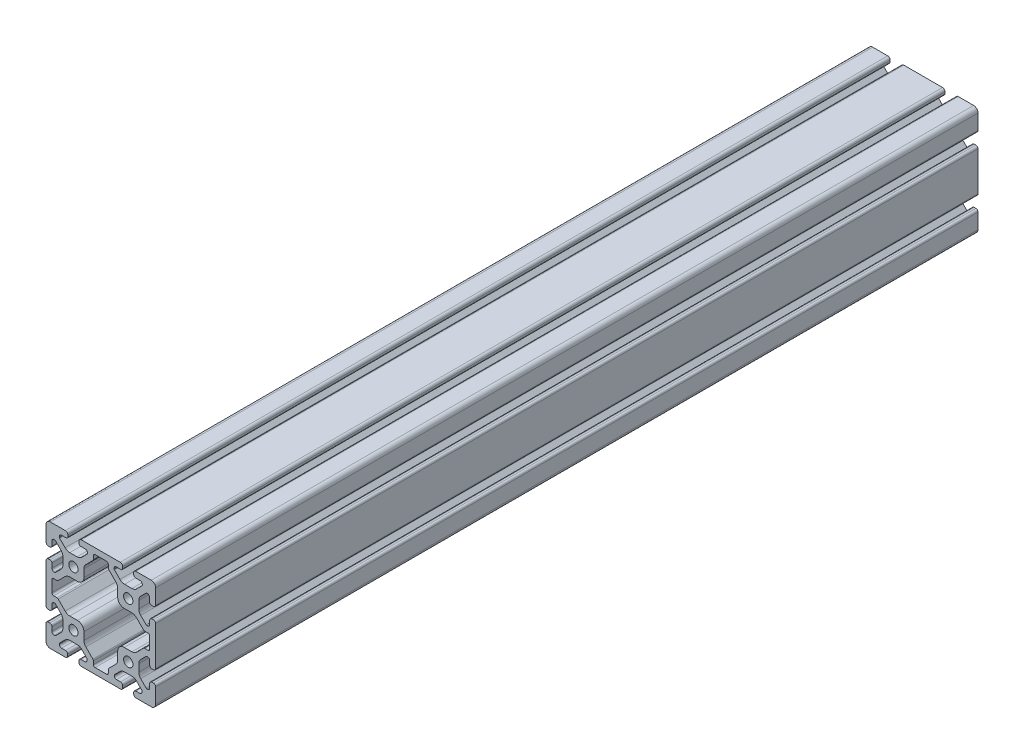
SolidWorks part; units mm, degrees
material "6061 Alloy"
ref_plane "Front Plane" through (0, 0, 0) normal (0, 0, 1) x (1, 0, 0)
ref_plane "Top Plane" through (0, 0, 0) normal (0, 1, 0) x (1, 0, 0)
ref_plane "Right Plane" through (0, 0, 0) normal (1, 0, 0) x (0, 0, -1)
sketch "Sketch1" plane through (0, 0, 0) normal (0, 0, 1) x (1, 0, 0)
  line L0 (0, -40) -> (0, 40) construction
  line L1 (0, 0) -> (-43.5804, 43.5804) construction
  line L2 (-20, 20) -> (-47.7323, 20) construction
  line L3 (-20, 20) -> (3.796, 43.796) construction
  line L4 (-20, 20) -> (-20, 43.5758) construction
  line L5 (-20, -27.7) -> (-20, -47.5576) construction
  line L131 (29.0912, 26.0365) -> (33.0827, 30.028)
  line L132 (27.7, 17.3222) -> (27.7, 22.6778)
  line L133 (29.0912, 13.9635) -> (33.0827, 9.972)
  line L134 (33.6201, 9.7494) -> (34.11, 9.7494)
  line L135 (35.68, 11.3194) -> (35.68, 14.2221)
  line L136 (37.25, 15.7921) -> (38.43, 15.7921)
  line L137 (40, 14.2221) -> (40, 7.0214)
  line L138 (40, 7.0214) -> (40, -7.0214)
  line L139 (40, -7.0214) -> (40, -14.2221)
  line L140 (38.43, -15.7921) -> (37.25, -15.7921)
  line L141 (35.68, -14.2221) -> (35.68, -11.3194)
  line L142 (33.6201, -9.7494) -> (34.11, -9.7494)
  line L143 (29.0912, -13.9635) -> (33.0827, -9.972)
  line L144 (27.7, -22.6778) -> (27.7, -17.3222)
  line L145 (29.0912, -26.0365) -> (33.0827, -30.028)
  line L146 (33.6201, -30.2506) -> (34.11, -30.2506)
  line L147 (35.68, -28.6806) -> (35.68, -25.7779)
  line L148 (37.25, -24.2079) -> (38.43, -24.2079)
  line L149 (40, -25.7779) -> (40, -33.0259)
  line L150 (40, -33.0259) -> (40, -36.83)
  line L151 (36.83, -40) -> (32.9998, -40)
  line L152 (32.9998, -40) -> (25.5696, -40)
  line L153 (23.9996, -38.43) -> (23.9996, -37.25)
  line L154 (25.5696, -35.68) -> (28.4723, -35.68)
  line L155 (30.0413, -34.0552) -> (30.0171, -33.3605)
  line L156 (29.7949, -32.8496) -> (26.0365, -29.0912)
  line L157 (17.3222, -27.7) -> (22.6778, -27.7)
  line L158 (10.035, -33.0197) -> (13.9635, -29.0912)
  line L159 (9.8124, -33.8926) -> (9.8124, -33.5571)
  line L160 (11.3824, -35.4626) -> (14.4246, -35.4626)
  line L161 (15.9946, -37.0326) -> (15.9946, -38.43)
  line L162 (14.4246, -40) -> (6.9987, -40)
  line L163 (6.9987, -40) -> (-6.9987, -40)
  line L164 (-6.9987, -40) -> (-14.4292, -40)
  line L165 (-15.9992, -38.43) -> (-15.9992, -37.25)
  line L166 (-14.4292, -35.68) -> (-11.5265, -35.68)
  line L167 (-9.9574, -34.0552) -> (-9.9816, -33.3618)
  line L168 (-10.2038, -32.8509) -> (-13.9635, -29.0912)
  line L169 (-22.6778, -27.7) -> (-17.3222, -27.7)
  line L170 (-30.028, -33.0827) -> (-26.0365, -29.0912)
  line L171 (-30.2506, -34.11) -> (-30.2506, -33.6201)
  line L172 (-28.6806, -35.68) -> (-25.7231, -35.68)
  line L173 (-24.1531, -37.25) -> (-24.1531, -38.43)
  line L174 (-25.7231, -40) -> (-33, -40)
  line L175 (-33, -40) -> (-36.83, -40)
  line L176 (-40, -36.83) -> (-40, -33.0191)
  line L177 (-40, -33.0191) -> (-40, -25.591)
  line L178 (-38.43, -24.021) -> (-37.25, -24.021)
  line L179 (-35.68, -28.4937) -> (-35.68, -25.591)
  line L180 (-34.0552, -30.0627) -> (-33.3827, -30.0392)
  line L181 (-32.8718, -29.8171) -> (-29.0912, -26.0365)
  line L182 (-27.7, -22.6778) -> (-27.7, -17.3222)
  line L183 (-29.0912, -13.9635) -> (-33.0827, -9.972)
  line L184 (-34.11, -9.7494) -> (-33.6201, -9.7494)
  line L185 (-35.68, -11.3194) -> (-35.68, -14.4473)
  line L186 (-38.43, -16.0173) -> (-37.25, -16.0173)
  line L187 (-40, -14.4473) -> (-40, -7.0169)
  line L188 (-40, -7.0169) -> (-40, 7.0169)
  line L189 (-40, 7.0169) -> (-40, 14.1348)
  line L190 (-38.1948, 15.94) -> (-36.9772, 15.94)
  line L191 (-35.68, 11.3194) -> (-35.68, 14.6428)
  line L192 (-34.11, 9.7494) -> (-33.6201, 9.7494)
  line L193 (-33.0827, 9.972) -> (-29.0912, 13.9635)
  line L194 (-27.7, 17.3222) -> (-27.7, 22.6778)
  line L195 (-29.0912, 26.0365) -> (-33.0827, 30.028)
  line L196 (-34.11, 30.2506) -> (-33.6201, 30.2506)
  line L197 (-35.68, 28.6806) -> (-35.68, 25.3572)
  line L198 (-38.1948, 24.06) -> (-36.9772, 24.06)
  line L199 (-40, 25.8652) -> (-40, 33.3181)
  line L200 (-40, 33.3181) -> (-40, 36.83)
  line L201 (-36.83, 40) -> (-33.0314, 40)
  line L202 (-33.0314, 40) -> (-25.8652, 40)
  line L203 (-24.06, 36.9772) -> (-24.06, 38.1948)
  line L204 (-25.3572, 35.68) -> (-28.7018, 35.68)
  line L205 (-30.285, 33.6069) -> (-30.285, 34.0968)
  line L206 (-30.0961, 33.1508) -> (-26.0365, 29.0912)
  line L207 (-22.6778, 27.7) -> (-17.3222, 27.7)
  line L208 (-13.9635, 29.0912) -> (-9.9039, 33.1508)
  line L209 (-9.715, 33.6069) -> (-9.715, 34.0968)
  line L210 (-14.6428, 35.68) -> (-11.2982, 35.68)
  line L211 (-15.94, 36.9772) -> (-15.94, 38.1948)
  line L212 (-14.1348, 40) -> (-6.9844, 40)
  line L213 (-6.9844, 40) -> (6.9844, 40)
  line L214 (6.9844, 40) -> (14.1348, 40)
  line L215 (15.94, 36.9772) -> (15.94, 38.1948)
  line L216 (14.6428, 35.68) -> (11.2982, 35.68)
  line L217 (9.715, 33.6069) -> (9.715, 34.0968)
  line L218 (9.9039, 33.1508) -> (13.9635, 29.0912)
  line L219 (17.3222, 27.7) -> (22.6778, 27.7)
  line L220 (26.0365, 29.0912) -> (30.028, 33.0827)
  line L221 (30.2506, 33.6201) -> (30.2506, 34.11)
  line L222 (25.5409, 35.679) -> (28.6258, 35.679)
  line L223 (23.9709, 37.249) -> (23.9709, 38.43)
  line L224 (25.5409, 40) -> (36.83, 40)
  line L226 (40, 36.83) -> (40, 32.9339)
  line L227 (40, 32.9339) -> (40, 25.7779)
  line L228 (38.43, 24.2079) -> (37.0956, 24.2079)
  line L229 (35.5256, 25.7779) -> (35.5256, 28.6806)
  line L230 (33.6201, 30.2506) -> (33.9556, 30.2506)
  line L231 (17.07, 12.32) -> (22.6578, 12.32)
  line L232 (26.0165, 10.9288) -> (31.1439, 5.8014)
  line L233 (32.0419, 5.4294) -> (34.41, 5.4294)
  line L234 (35.68, -4.1594) -> (35.68, 4.1594)
  line L235 (32.0419, -5.4294) -> (34.41, -5.4294)
  line L236 (26.0165, -10.9288) -> (31.1439, -5.8014)
  line L237 (17.07, -12.32) -> (22.6578, -12.32)
  line L238 (12.32, -22.6578) -> (12.32, -17.07)
  line L239 (5.8014, -31.1439) -> (10.9288, -26.0165)
  line L240 (5.4294, -34.41) -> (5.4294, -32.0419)
  line L241 (-4.1594, -35.68) -> (4.1594, -35.68)
  line L242 (-5.4294, -34.41) -> (-5.4294, -32.0419)
  line L243 (-5.8014, -31.1439) -> (-10.9288, -26.0165)
  line L244 (-12.32, -22.6578) -> (-12.32, -17.07)
  line L245 (-22.6578, -12.32) -> (-17.07, -12.32)
  line L246 (-26.0165, -10.9288) -> (-31.1439, -5.8014)
  line L247 (-34.41, -5.4294) -> (-32.0419, -5.4294)
  line L248 (-35.68, -4.1594) -> (-35.68, 4.1594)
  line L249 (-34.41, 5.4294) -> (-32.0419, 5.4294)
  line L250 (-31.1439, 5.8014) -> (-26.0165, 10.9288)
  line L251 (-22.6578, 12.32) -> (-17.07, 12.32)
  line L252 (-12.32, 17.07) -> (-12.32, 22.6578)
  line L253 (-10.9288, 26.0165) -> (-5.8014, 31.1439)
  line L254 (-5.4294, 32.0419) -> (-5.4294, 34.41)
  line L255 (-4.1594, 35.68) -> (4.1594, 35.68)
  line L256 (5.4294, 32.0419) -> (5.4294, 34.41)
  line L257 (5.8014, 31.1439) -> (10.9288, 26.0165)
  line L258 (12.32, 17.07) -> (12.32, 22.6578)
  line L260 (-40, 0) -> (40, 0) construction
  circle A116 centre (-20, 20) radius 3.4
  circle A117 centre (20, 20) radius 3.4
  circle A118 centre (20, -20) radius 3.4
  circle A119 centre (-20, -20) radius 3.4
  arc A120 (29.0912, 26.0365) -> (27.7, 22.6778) centre (32.45, 22.6778) ccw
  arc A121 (27.7, 17.3222) -> (29.0912, 13.9635) centre (32.45, 17.3222) ccw
  arc A122 (33.0827, 9.972) -> (33.6201, 9.7494) centre (33.6201, 10.5094) ccw
  arc A123 (34.11, 9.7494) -> (35.68, 11.3194) centre (34.11, 11.3194) ccw
  arc A124 (37.25, 15.7921) -> (35.68, 14.2221) centre (37.25, 14.2221) ccw
  arc A125 (40, 14.2221) -> (38.43, 15.7921) centre (38.43, 14.2221) ccw
  arc A126 (38.43, -15.7921) -> (40, -14.2221) centre (38.43, -14.2221) ccw
  arc A127 (35.68, -14.2221) -> (37.25, -15.7921) centre (37.25, -14.2221) ccw
  arc A128 (35.68, -11.3194) -> (34.11, -9.7494) centre (34.11, -11.3194) ccw
  arc A129 (33.6201, -9.7494) -> (33.0827, -9.972) centre (33.6201, -10.5094) ccw
  arc A130 (29.0912, -13.9635) -> (27.7, -17.3222) centre (32.45, -17.3222) ccw
  arc A131 (27.7, -22.6778) -> (29.0912, -26.0365) centre (32.45, -22.6778) ccw
  arc A132 (33.0827, -30.028) -> (33.6201, -30.2506) centre (33.6201, -29.4906) ccw
  arc A133 (34.11, -30.2506) -> (35.68, -28.6806) centre (34.11, -28.6806) ccw
  arc A134 (37.25, -24.2079) -> (35.68, -25.7779) centre (37.25, -25.7779) ccw
  arc A135 (40, -25.7779) -> (38.43, -24.2079) centre (38.43, -25.7779) ccw
  arc A136 (36.83, -40) -> (40, -36.83) centre (36.83, -36.83) ccw
  arc A137 (23.9996, -38.43) -> (25.5696, -40) centre (25.5696, -38.43) ccw
  arc A138 (25.5696, -35.68) -> (23.9996, -37.25) centre (25.5696, -37.25) ccw
  arc A139 (28.4723, -35.68) -> (30.0413, -34.0552) centre (28.4723, -34.11) ccw
  arc A140 (30.0171, -33.3605) -> (29.7949, -32.8496) centre (29.2575, -33.387) ccw
  arc A141 (26.0365, -29.0912) -> (22.6778, -27.7) centre (22.6778, -32.45) ccw
  arc A142 (17.3222, -27.7) -> (13.9635, -29.0912) centre (17.3222, -32.45) ccw
  arc A143 (10.035, -33.0197) -> (9.8124, -33.5571) centre (10.5724, -33.5571) ccw
  arc A144 (9.8124, -33.8926) -> (11.3824, -35.4626) centre (11.3824, -33.8926) ccw
  arc A145 (15.9946, -37.0326) -> (14.4246, -35.4626) centre (14.4246, -37.0326) ccw
  arc A146 (14.4246, -40) -> (15.9946, -38.43) centre (14.4246, -38.43) ccw
  arc A147 (-15.9992, -38.43) -> (-14.4292, -40) centre (-14.4292, -38.43) ccw
  arc A148 (-14.4292, -35.68) -> (-15.9992, -37.25) centre (-14.4292, -37.25) ccw
  arc A149 (-11.5265, -35.68) -> (-9.9574, -34.0552) centre (-11.5265, -34.11) ccw
  arc A150 (-9.9816, -33.3618) -> (-10.2038, -32.8509) centre (-10.7412, -33.3883) ccw
  arc A151 (-13.9635, -29.0912) -> (-17.3222, -27.7) centre (-17.3222, -32.45) ccw
  arc A152 (-22.6778, -27.7) -> (-26.0365, -29.0912) centre (-22.6778, -32.45) ccw
  arc A153 (-30.028, -33.0827) -> (-30.2506, -33.6201) centre (-29.4906, -33.6201) ccw
  arc A154 (-30.2506, -34.11) -> (-28.6806, -35.68) centre (-28.6806, -34.11) ccw
  arc A155 (-24.1531, -37.25) -> (-25.7231, -35.68) centre (-25.7231, -37.25) ccw
  arc A156 (-25.7231, -40) -> (-24.1531, -38.43) centre (-25.7231, -38.43) ccw
  arc A157 (-40, -36.83) -> (-36.83, -40) centre (-36.83, -36.83) ccw
  arc A158 (-38.43, -24.021) -> (-40, -25.591) centre (-38.43, -25.591) ccw
  arc A159 (-35.68, -25.591) -> (-37.25, -24.021) centre (-37.25, -25.591) ccw
  arc A160 (-35.68, -28.4937) -> (-34.0552, -30.0627) centre (-34.11, -28.4937) ccw
  arc A161 (-33.3827, -30.0392) -> (-32.8718, -29.8171) centre (-33.4092, -29.2797) ccw
  arc A162 (-29.0912, -26.0365) -> (-27.7, -22.6778) centre (-32.45, -22.6778) ccw
  arc A163 (-27.7, -17.3222) -> (-29.0912, -13.9635) centre (-32.45, -17.3222) ccw
  arc A164 (-33.0827, -9.972) -> (-33.6201, -9.7494) centre (-33.6201, -10.5094) ccw
  arc A165 (-34.11, -9.7494) -> (-35.68, -11.3194) centre (-34.11, -11.3194) ccw
  arc A166 (-37.25, -16.0173) -> (-35.68, -14.4473) centre (-37.25, -14.4473) ccw
  arc A167 (-40, -14.4473) -> (-38.43, -16.0173) centre (-38.43, -14.4473) ccw
  arc A168 (-38.1948, 15.94) -> (-40, 14.1348) centre (-38.1948, 14.1348) ccw
  arc A169 (-35.68, 14.6428) -> (-36.9772, 15.94) centre (-36.9772, 14.6428) ccw
  arc A170 (-35.68, 11.3194) -> (-34.11, 9.7494) centre (-34.11, 11.3194) ccw
  arc A171 (-33.6201, 9.7494) -> (-33.0827, 9.972) centre (-33.6201, 10.5094) ccw
  arc A172 (-29.0912, 13.9635) -> (-27.7, 17.3222) centre (-32.45, 17.3222) ccw
  arc A173 (-27.7, 22.6778) -> (-29.0912, 26.0365) centre (-32.45, 22.6778) ccw
  arc A174 (-33.0827, 30.028) -> (-33.6201, 30.2506) centre (-33.6201, 29.4906) ccw
  arc A175 (-34.11, 30.2506) -> (-35.68, 28.6806) centre (-34.11, 28.6806) ccw
  arc A176 (-36.9772, 24.06) -> (-35.68, 25.3572) centre (-36.9772, 25.3572) ccw
  arc A177 (-40, 25.8652) -> (-38.1948, 24.06) centre (-38.1948, 25.8652) ccw
  arc A178 (-36.83, 40) -> (-40, 36.83) centre (-36.83, 36.83) ccw
  arc A179 (-24.06, 38.1948) -> (-25.8652, 40) centre (-25.8652, 38.1948) ccw
  arc A180 (-25.3572, 35.68) -> (-24.06, 36.9772) centre (-25.3572, 36.9772) ccw
  arc A181 (-28.7018, 35.68) -> (-30.285, 34.0968) centre (-28.7018, 34.0968) ccw
  arc A182 (-30.285, 33.6069) -> (-30.0961, 33.1508) centre (-29.6399, 33.6069) ccw
  arc A183 (-26.0365, 29.0912) -> (-22.6778, 27.7) centre (-22.6778, 32.45) ccw
  arc A184 (-17.3222, 27.7) -> (-13.9635, 29.0912) centre (-17.3222, 32.45) ccw
  arc A185 (-9.9039, 33.1508) -> (-9.715, 33.6069) centre (-10.3601, 33.6069) ccw
  arc A186 (-9.715, 34.0968) -> (-11.2982, 35.68) centre (-11.2982, 34.0968) ccw
  arc A187 (-15.94, 36.9772) -> (-14.6428, 35.68) centre (-14.6428, 36.9772) ccw
  arc A188 (-14.1348, 40) -> (-15.94, 38.1948) centre (-14.1348, 38.1948) ccw
  arc A189 (15.94, 38.1948) -> (14.1348, 40) centre (14.1348, 38.1948) ccw
  arc A190 (14.6428, 35.68) -> (15.94, 36.9772) centre (14.6428, 36.9772) ccw
  arc A191 (11.2982, 35.68) -> (9.715, 34.0968) centre (11.2982, 34.0968) ccw
  arc A192 (9.715, 33.6069) -> (9.9039, 33.1508) centre (10.3601, 33.6069) ccw
  arc A193 (13.9635, 29.0912) -> (17.3222, 27.7) centre (17.3222, 32.45) ccw
  arc A194 (22.6778, 27.7) -> (26.0365, 29.0912) centre (22.6778, 32.45) ccw
  arc A195 (30.028, 33.0827) -> (30.2506, 33.6201) centre (29.4906, 33.6201) ccw
  arc A196 (30.2506, 34.11) -> (28.6258, 35.679) centre (28.6806, 34.11) ccw
  arc A197 (23.9709, 37.249) -> (25.5409, 35.679) centre (25.5409, 37.249) ccw
  arc A198 (25.5409, 40) -> (23.9709, 38.43) centre (25.5409, 38.43) ccw
  arc A199 (40, 36.83) -> (36.83, 40) centre (36.83, 36.83) ccw
  arc A200 (38.43, 24.2079) -> (40, 25.7779) centre (38.43, 25.7779) ccw
  arc A201 (35.5256, 25.7779) -> (37.0956, 24.2079) centre (37.0956, 25.7779) ccw
  arc A202 (35.5256, 28.6806) -> (33.9556, 30.2506) centre (33.9556, 28.6806) ccw
  arc A203 (33.6201, 30.2506) -> (33.0827, 30.028) centre (33.6201, 29.4906) ccw
  arc A204 (26.0165, 10.9288) -> (22.6578, 12.32) centre (22.6578, 7.57) ccw
  arc A205 (31.1439, 5.8014) -> (32.0419, 5.4294) centre (32.0419, 6.6994) ccw
  arc A206 (35.68, 4.1594) -> (34.41, 5.4294) centre (34.41, 4.1594) ccw
  arc A207 (34.41, -5.4294) -> (35.68, -4.1594) centre (34.41, -4.1594) ccw
  arc A208 (32.0419, -5.4294) -> (31.1439, -5.8014) centre (32.0419, -6.6994) ccw
  arc A209 (22.6578, -12.32) -> (26.0165, -10.9288) centre (22.6578, -7.57) ccw
  arc A210 (17.07, -12.32) -> (12.32, -17.07) centre (17.07, -17.07) ccw
  arc A211 (10.9288, -26.0165) -> (12.32, -22.6578) centre (7.57, -22.6578) ccw
  arc A212 (5.8014, -31.1439) -> (5.4294, -32.0419) centre (6.6994, -32.0419) ccw
  arc A213 (4.1594, -35.68) -> (5.4294, -34.41) centre (4.1594, -34.41) ccw
  arc A214 (-5.4294, -34.41) -> (-4.1594, -35.68) centre (-4.1594, -34.41) ccw
  arc A215 (-5.4294, -32.0419) -> (-5.8014, -31.1439) centre (-6.6994, -32.0419) ccw
  arc A216 (-12.32, -22.6578) -> (-10.9288, -26.0165) centre (-7.57, -22.6578) ccw
  arc A217 (-12.32, -17.07) -> (-17.07, -12.32) centre (-17.07, -17.07) ccw
  arc A218 (-26.0165, -10.9288) -> (-22.6578, -12.32) centre (-22.6578, -7.57) ccw
  arc A219 (-31.1439, -5.8014) -> (-32.0419, -5.4294) centre (-32.0419, -6.6994) ccw
  arc A220 (-35.68, -4.1594) -> (-34.41, -5.4294) centre (-34.41, -4.1594) ccw
  arc A221 (-34.41, 5.4294) -> (-35.68, 4.1594) centre (-34.41, 4.1594) ccw
  arc A222 (-32.0419, 5.4294) -> (-31.1439, 5.8014) centre (-32.0419, 6.6994) ccw
  arc A223 (-22.6578, 12.32) -> (-26.0165, 10.9288) centre (-22.6578, 7.57) ccw
  arc A224 (-17.07, 12.32) -> (-12.32, 17.07) centre (-17.07, 17.07) ccw
  arc A225 (-10.9288, 26.0165) -> (-12.32, 22.6578) centre (-7.57, 22.6578) ccw
  arc A226 (-5.8014, 31.1439) -> (-5.4294, 32.0419) centre (-6.6994, 32.0419) ccw
  arc A227 (-4.1594, 35.68) -> (-5.4294, 34.41) centre (-4.1594, 34.41) ccw
  arc A228 (5.4294, 34.41) -> (4.1594, 35.68) centre (4.1594, 34.41) ccw
  arc A229 (5.4294, 32.0419) -> (5.8014, 31.1439) centre (6.6994, 32.0419) ccw
  arc A230 (12.32, 22.6578) -> (10.9288, 26.0165) centre (7.57, 22.6578) ccw
  arc A231 (12.32, 17.07) -> (17.07, 12.32) centre (17.07, 17.07) ccw
  dimension "D8" = 6.8
  dimension "D1" = 80
  dimension "D2" = 40
  dimension "D3" = 20
  dimension "D4" = 20.57
  dimension "D5" = 4.32
  dimension "D6" = 4.32
  dimension "D7" = 8.12
  dimension "D9" = 4.32
  dimension "D10" = 12.3
extrude "Extrude1" add sketch "Sketch1" against normal blind 600
